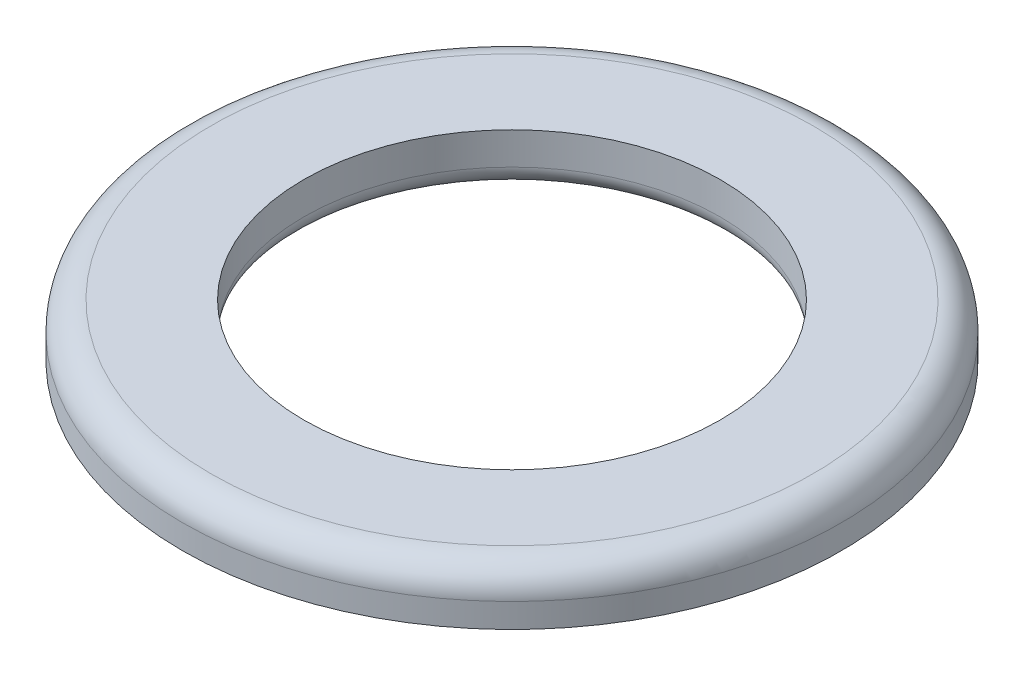
SolidWorks part; units mm, degrees
ref_plane "Front Plane" through (0, 0, 0) normal (0, 0, 1) x (1, 0, 0)
ref_plane "Top Plane" through (0, 0, 0) normal (0, 1, 0) x (1, 0, 0)
ref_plane "Right Plane" through (0, 0, 0) normal (1, 0, 0) x (0, 0, -1)
sketch "Sketch1" plane through (0, 0, 0) normal (0, 1, 0) x (1, 0, 0)
  circle A0 centre (0, 0) radius 8.15
  circle A1 centre (0, 0) radius 5.15
  dimension "D1" = 16.3
  dimension "D2" = 10.3
extrude "Boss-Extrude1" add sketch "Sketch1" along normal blind 1.3
fillet "Fillet3" radius 0.7 1 edges at (0, 1.3, 8.15)
fillet "Fillet4" radius 0.5 1 edges at (0, 0, 5.15)
